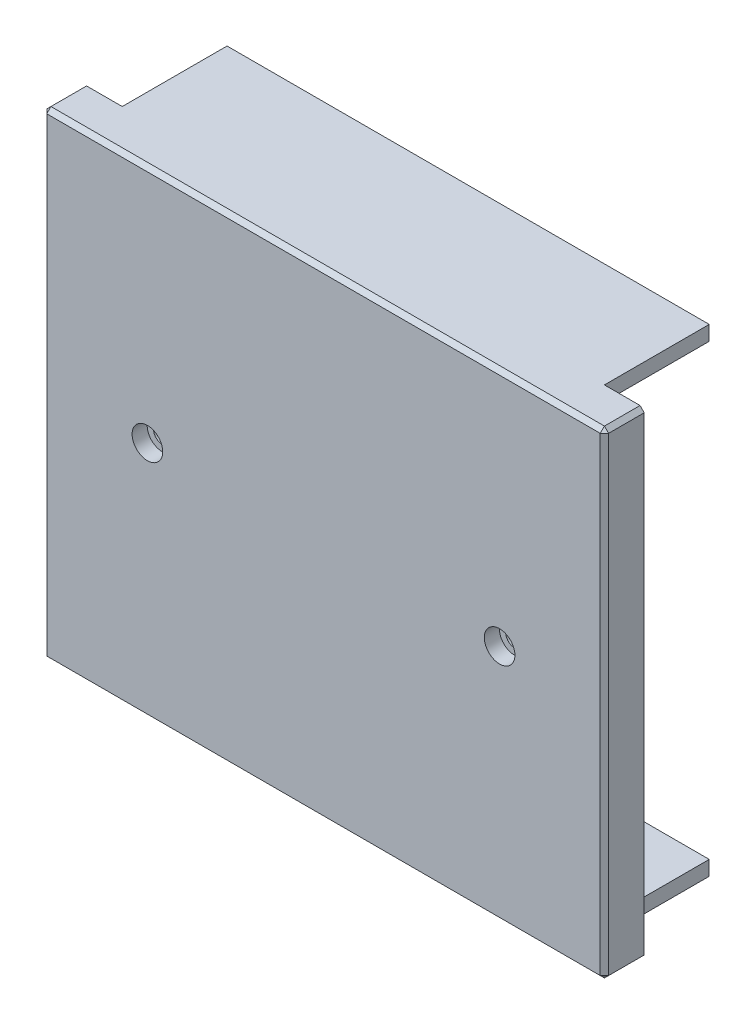
SolidWorks part; units mm, degrees
ref_plane "Front Plane" through (0, 0, 0) normal (0, 0, 1) x (1, 0, 0)
ref_plane "Top Plane" through (0, 0, 0) normal (0, 1, 0) x (1, 0, 0)
ref_plane "Right Plane" through (0, 0, 0) normal (1, 0, 0) x (0, 0, -1)
sketch "Sketch1" plane through (0, 0, 0) normal (0, 0, 1) x (1, 0, 0)
  line L1 (0, 0) -> (134, 0)
  line L2 (0, 0) -> (0, 114)
  line L3 (0, 114) -> (134, 114)
  line L4 (134, 0) -> (134, 114)
  dimension "D1" = 134
  dimension "D2" = 114
extrude "Boss-Extrude1" add sketch "Sketch1" along normal blind 9.5
sketch "Sketch2" plane through (0, 0, 0) normal (0, 0, -1) x (-1, 0, 0)
  line L0 (-67, 114) -> (-67, 0) construction
  line L1 (-134, 114) -> (0, 114) construction
  line L2 (0, 0) -> (-134, 0) construction
  line L3 (-67, 114) -> (-124.5, 114)
  line L4 (-124.5, 114) -> (-124.5, 110.5)
  line L5 (-124.5, 110.5) -> (-9.5, 110.5)
  line L6 (-9.5, 110.5) -> (-9.5, 114)
  line L7 (-9.5, 114) -> (-67, 114)
  line L9 (-124.5, 0) -> (-9.5, 0)
  line L10 (-124.5, 0) -> (-124.5, 3.5)
  line L11 (-124.5, 3.5) -> (-9.5, 3.5)
  line L12 (-9.5, 0) -> (-9.5, 3.5)
  dimension "D1" = 3.5
  dimension "D2" = 115
extrude "Boss-Extrude2" add sketch "Sketch2" along normal blind 25
sketch "Sketch3" plane through (0, 0, 9.5) normal (0, 0, 1) x (1, 0, 0)
  line L0 (0, 57) -> (134, 57) construction
  line L1 (0, 114) -> (0, 0) construction
  line L2 (134, 0) -> (134, 114) construction
  circle A0 centre (25, 57) radius 2.15
  circle A1 centre (109, 57) radius 2.15
  dimension "D1" = 4.3
  dimension "D3" = 25
  dimension "D2" = 25
extrude "Cut-Extrude1" cut sketch "Sketch3" against normal through all
sketch "Sketch4" plane through (0, 0, 9.5) normal (0, 0, 1) x (1, 0, 0)
  circle A0 centre (25, 57) radius 3.65
  circle A1 centre (109, 57) radius 3.65
  dimension "D1" = 7.3
extrude "Cut-Extrude2" cut sketch "Sketch4" against normal blind 3.6
chamfer "Chamfer1" distance 1 angle 45 8 edges at (0, 0, 4.75) (0, 114, 4.75) (134, 114, 4.75) (134, 0, 4.75) (134, 57, 9.5) (67, 0, 9.5) (0, 57, 9.5) (67, 114, 9.5)
